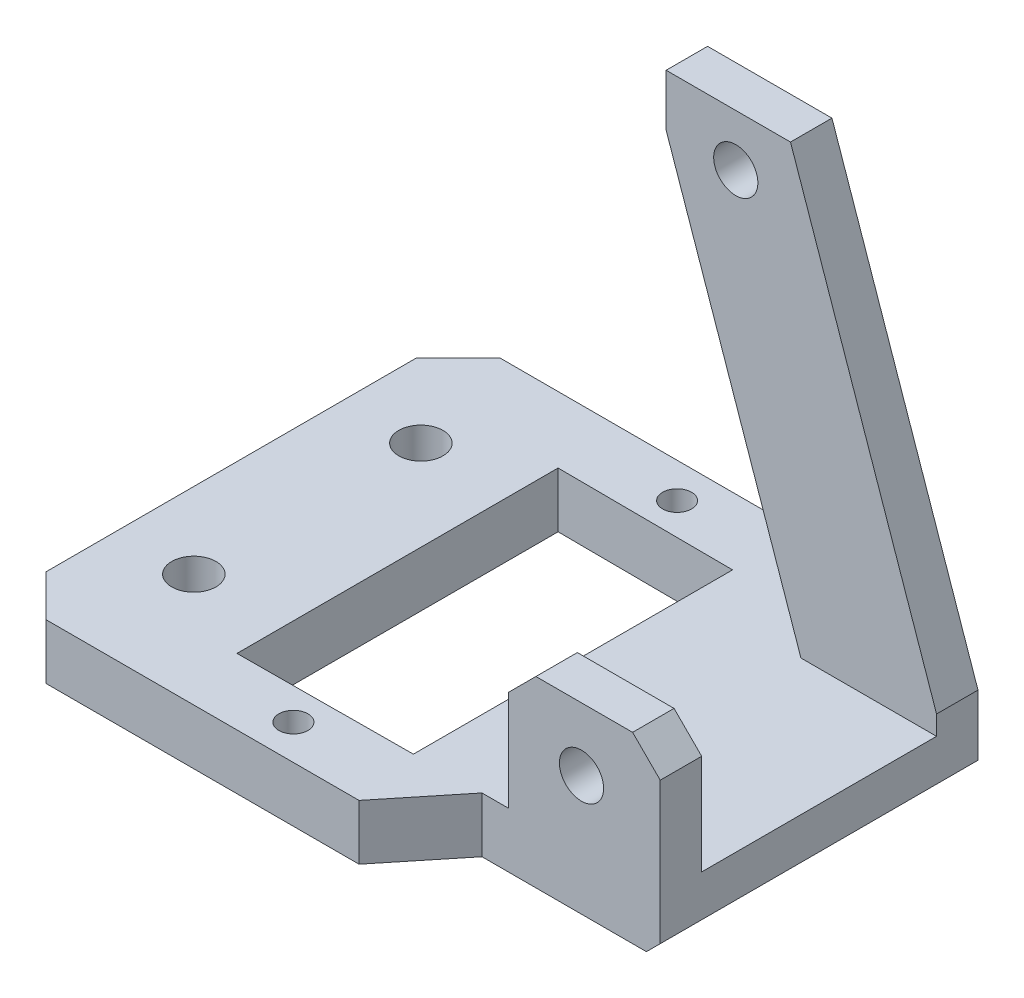
SolidWorks part; units mm, degrees
ref_plane "Plan de face" through (0, 0, 0) normal (0, 0, 1) x (1, 0, 0)
ref_plane "Plan de dessus" through (0, 0, 0) normal (0, 1, 0) x (1, 0, 0)
ref_plane "Plan de droite" through (0, 0, 0) normal (1, 0, 0) x (0, 0, -1)
sketch "Esquisse2" plane through (0, 0, 0) normal (0, 1, 0) x (1, 0, 0)
  line L0 (17.5, 0) -> (17.5, 11.5)
  line L1 (-17.4196, 0) -> (17.4196, 0) construction
  line L2 (17.5, 0) -> (17.5, -11.5)
  line L3 (0, -11) -> (0, 11) construction
  line L4 (-17.5, 0) -> (-17.5, -11.5)
  line L5 (-17.5, 0) -> (-17.5, 11.5)
  line L6 (-17.5, 11.5) -> (17.5, 11.5)
  line L7 (-17.5, -11.5) -> (17.5, -11.5)
  dimension "D1" = 23
  dimension "D2" = 35
extrude "Boss.-Extru.1" add sketch "Esquisse2" along normal blind 4
sketch "Esquisse4" plane through (0, 0, 11.5) normal (0, 0, 1) x (1, 0, 0)
  line L0 (17.5, 2.2508) -> (17.5, 13.2508)
  line L1 (17.5, 4) -> (17.5, 0) construction
  line L2 (17.5, 13.2508) -> (6.5, 13.2508)
  line L3 (6.5, 13.2508) -> (6.5, 2.2508)
  line L4 (6.5, 2.2508) -> (17.5, 2.2508)
  dimension "D1" = 11
  dimension "D2" = 11
extrude "Boss.-Extru.2" add sketch "Esquisse4" against normal blind 3
sketch "Esquisse5" plane through (0, 0, -11.5) normal (0, 0, -1) x (-1, 0, 0)
  line L0 (-17.5, 2.4943) -> (-17.5, 5.3991)
  line L1 (-17.5, 4) -> (-17.5, 0) construction
  line L2 (-17.5, 4) -> (-17.5, 13.2508) construction
  line L3 (-17.5, 5.3991) -> (-6.9283, 35.9661)
  line L4 (-6.9283, 35.9661) -> (2.0723, 35.9661)
  line L5 (2.0723, 35.9661) -> (2.0723, 32.2104)
  line L7 (-17.5, 4) -> (17.5, 4) construction
  line L8 (2.0723, 32.2104) -> (-7.6844, 4)
  line L9 (-7.6844, 4) -> (-7.6844, 2.4943)
  line L10 (-7.6844, 2.4943) -> (-17.5, 2.4943)
extrude "Boss.-Extru.3" add sketch "Esquisse5" against normal blind 3
sketch "Esquisse6" plane through (0, 0, 11.5) normal (0, 0, 1) x (1, 0, 0)
  circle A0 centre (11.8027, 8.6833) radius 1.6
  dimension "D1" = 3.2
sketch "Esquisse7" plane through (0, 0, -11.5) normal (0, 0, -1) x (-1, 0, 0)
  circle A0 centre (-2.9672, 32.2271) radius 1.6
  dimension "D1" = 3.2
extrude "Enlèv. mat.-Extru.1" cut sketch "Esquisse6" against normal blind 10
extrude "Enlèv. mat.-Extru.2" cut sketch "Esquisse7" against normal blind 10
sketch "Esquisse8" plane through (0, 0, 0) normal (0, -1, 0) x (1, 0, 0)
  line L0 (4.5984, -11.5) -> (0.6174, -16.4168)
  line L1 (-2.0723, -11.5) -> (6.9283, -11.5) construction
  line L2 (0.6174, -16.4168) -> (-25.0416, -16.4168)
  line L3 (-25.0416, -16.4168) -> (-25.0416, 16.4168)
  line L4 (4.5984, -11.5) -> (4.5984, 11.5)
  line L5 (19.25, 0) -> (-19.25, 0) construction
  line L6 (0.6174, 16.4168) -> (-25.0416, 16.4168)
  line L7 (4.5984, 11.5) -> (0.6174, 16.4168)
  point P10 (4.5984, 0)
  point P11 (-25.0416, 0)
  dimension "D1" = 25.6591
  dimension "D2" = 32.8335
extrude "Boss.-Extru.4" add sketch "Esquisse8" against normal blind 4
sketch "Esquisse10" plane through (0, 4, 0) normal (0, 1, 0) x (1, 0, 0)
  line L0 (-13.0156, -11.6229) -> (-13.0156, 11.6229)
  line L1 (-19.7813, 0) -> (19.7813, 0) construction
  line L2 (-13.0156, 11.6229) -> (-0.3156, 11.55)
  line L3 (-0.3156, 11.55) -> (-0.3156, -11.55)
  line L4 (-13.0156, -11.6229) -> (-0.3156, -11.55)
  line L5 (7.6844, 8.5) -> (7.6844, 11.5) construction
  line L6 (-25.0416, -16.4168) -> (-25.0416, 16.4168) construction
  line L7 (0.6174, -16.4168) -> (-25.0416, -16.4168) construction
  line L8 (-25.0416, 16.4168) -> (0.6174, 16.4168) construction
  circle A0 centre (-6.6656, -13.8865) radius 1.05
  circle A1 centre (-6.6656, 13.8865) radius 1.05
  circle A2 centre (-19.5416, 8.2168) radius 1.6
  circle A3 centre (-19.5416, -8.2168) radius 1.6
  point P7 (-0.3156, 0)
  point P8 (-13.0156, 0)
  dimension "D3" = 2.3
  dimension "D8" = 2.1
  dimension "D9" = 3.2
  dimension "D1" = 23.1
  dimension "D2" = 2.3
  dimension "D4" = 8
  dimension "D5" = 6.35
  dimension "D6" = 6.35
  dimension "D7" = 12.7
  dimension "D10" = 5.5
  dimension "D11" = 5.5
  dimension "D12" = 8.2
  dimension "D13" = 8.2
extrude "Enlèv. mat.-Extru.3" cut sketch "Esquisse10" against normal blind 4
chamfer "Chanfrein1" distance 1 angle 45 1 edges at (17.5, 0, 0)
chamfer "Chanfrein2" distance 3 angle 45 2 edges at (-25.0416, 2, -16.4168) (-25.0416, 2, 16.4168)
chamfer "Chanfrein3" distance 2 angle 45 2 edges at (17.5, 13.2508, 10) (6.5, 13.2508, 10)
